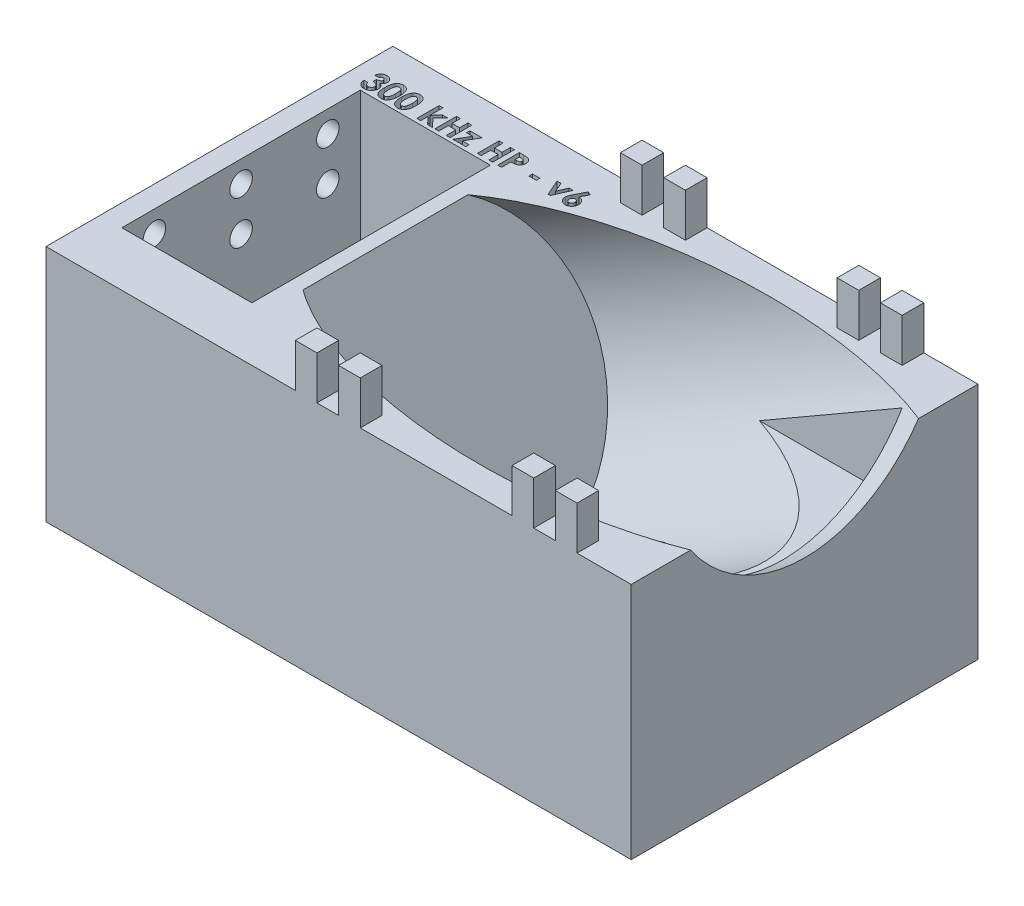
SolidWorks part; units mm, degrees
ref_plane "Front Plane" through (0, 0, 0) normal (0, 0, 1) x (1, 0, 0)
ref_plane "Top Plane" through (0, 0, 0) normal (0, 1, 0) x (1, 0, 0)
ref_plane "Right Plane" through (0, 0, 0) normal (1, 0, 0) x (0, 0, -1)
sketch "Sketch1" plane through (0, 0, 0) normal (0, 0, 1) x (1, 0, 0)
  line L1 (-139.7, -127) -> (88.9, -127)
  line L2 (-139.7, -127) -> (-139.7, 0)
  line L3 (-139.7, 0) -> (88.9, 0)
  line L4 (88.9, -127) -> (88.9, 0)
  line L5 (-139.7, -127) -> (88.9, 0) construction
  line L6 (-139.7, 0) -> (88.9, -127) construction
  point P0 (0, 0)
  dimension "D1" = 228.6
  dimension "D2" = 127
  dimension "D3" = 88.9
extrude "Boss-Extrude1" add sketch "Sketch1" along normal mid plane 101.6
sketch "Sketch10" plane through (0, -127, 0) normal (0, -1, 0) x (1, 0, 0)
  circle A0 centre (0, 0) radius 12.7
  dimension "D1" = 25.4
extrude "Cut-Extrude6" cut sketch "Sketch10" against normal through all
sketch "Sketch2" plane through (0, 0, 0) normal (0, 0, 1) x (1, 0, 0)
  line L0 (-48.125, -30.325) -> (0, -2.54) construction
  line L1 (0, 46.5867) -> (-47.9201, 18.9201)
  line L2 (-50.1425, -26.8306) -> (-69.3975, 6.5201)
  line L3 (-69.3975, 6.5201) -> (-47.9201, 18.9201)
  line L4 (-50.1425, -26.8306) -> (-48.125, -30.325)
  line L5 (-26.6476, -17.925) -> (-47.9201, 18.9201) construction
  line L7 (0, -2.54) -> (87.9882, 48.26)
  line L8 (-83.8, -2.54) -> (0, -2.54) construction
  line L10 (0, -2.54) -> (-48.125, -30.325)
  line L11 (88.9, 0) -> (-139.7, 0) construction
  line L12 (87.9882, 48.26) -> (66.7157, 85.1051)
  line L13 (0, 46.5867) -> (0, -2.54) construction
  line L17 (66.7157, 85.1051) -> (0, 46.5867)
  point P23 (-26.6476, -17.925)
  dimension "D1" = 30
  dimension "D2" = 24.8
  dimension "D3" = 2.54
  dimension "D4" = 30.77
  dimension "D5" = 42.545
  dimension "D6" = 101.6
revolve "Cut-Revolve1" cut sketch "Sketch2" angle 360 about L0
sketch "Sketch11" plane through (0, -127, 0) normal (0, -1, 0) x (1, 0, 0)
  line L1 (13, 13) -> (-13, 13)
  line L2 (13, 13) -> (13, -13)
  line L3 (13, -13) -> (-13, -13)
  line L4 (-13, 13) -> (-13, -13)
  line L5 (13, 13) -> (-13, -13) construction
  line L6 (13, -13) -> (-13, 13) construction
  point P0 (0, 0)
  dimension "D1" = 26
sketch "Sketch13" plane through (0, 0, 0) normal (0, 1, 0) x (1, 0, 0)
  line L0 (88.9, 50.8) -> (-139.7, 50.8) construction
  line L1 (-41.275, 50.8) -> (-34.925, 50.8)
  line L2 (-41.275, 50.8) -> (-41.275, 44.45)
  line L3 (-41.275, 44.45) -> (-34.925, 44.45)
  line L4 (-34.925, 50.8) -> (-34.925, 44.45)
  line L5 (0, 0) -> (42.9001, 0) construction
  line L6 (-28.575, 50.8) -> (-22.225, 50.8)
  line L7 (-28.575, 50.8) -> (-28.575, 44.45)
  line L8 (-28.575, 44.45) -> (-22.225, 44.45)
  line L9 (-22.225, 50.8) -> (-22.225, 44.45)
  line L10 (0, 0) -> (0, -29.3087) construction
  line L11 (22.225, 50.8) -> (22.225, 44.45)
  line L12 (28.575, 44.45) -> (22.225, 44.45)
  line L13 (28.575, 50.8) -> (28.575, 44.45)
  line L14 (28.575, 50.8) -> (22.225, 50.8)
  line L15 (34.925, 50.8) -> (34.925, 44.45)
  line L16 (41.275, 44.45) -> (34.925, 44.45)
  line L17 (41.275, 50.8) -> (41.275, 44.45)
  line L18 (41.275, 50.8) -> (34.925, 50.8)
  line L19 (41.275, -50.8) -> (34.925, -50.8)
  line L20 (41.275, -50.8) -> (41.275, -44.45)
  line L21 (41.275, -44.45) -> (34.925, -44.45)
  line L22 (34.925, -50.8) -> (34.925, -44.45)
  line L23 (28.575, -50.8) -> (22.225, -50.8)
  line L24 (28.575, -50.8) -> (28.575, -44.45)
  line L25 (28.575, -44.45) -> (22.225, -44.45)
  line L26 (22.225, -50.8) -> (22.225, -44.45)
  line L27 (-22.225, -50.8) -> (-22.225, -44.45)
  line L28 (-28.575, -44.45) -> (-22.225, -44.45)
  line L29 (-28.575, -50.8) -> (-28.575, -44.45)
  line L30 (-28.575, -50.8) -> (-22.225, -50.8)
  line L31 (-34.925, -50.8) -> (-34.925, -44.45)
  line L32 (-41.275, -44.45) -> (-34.925, -44.45)
  line L33 (-41.275, -50.8) -> (-41.275, -44.45)
  line L34 (-41.275, -50.8) -> (-34.925, -50.8)
  point P18 (-25.4, 50.8)
  point P20 (-38.1, 50.8)
  dimension "D1" = 25.4
  dimension "D2" = 12.7
  dimension "D3" = 6.35
extrude "Boss-Extrude3" add sketch "Sketch13" along normal blind 12.7
sketch "Sketch22" plane through (0, 0, 0) normal (0, 1, 0) x (1, 0, 0)
  line L0 (-41.275, -50.8) -> (-139.7, -50.8) construction
  line L1 (-139.7, 50.8) -> (-114.3, 50.8)
  line L2 (-139.7, 50.8) -> (-139.7, -50.8)
  line L3 (-139.7, -50.8) -> (-114.3, -50.8)
  line L4 (-114.3, 50.8) -> (-114.3, -50.8)
  dimension "D1" = 25.4
extrude "Cut-Extrude17" cut sketch "Sketch22" against normal through all
sketch "Sketch23" plane through (0, -127, 0) normal (0, -1, 0) x (1, 0, 0)
  line L0 (-127, 127) -> (127, -127) construction
  line L1 (-127, 127) -> (127, 127)
  line L2 (-127, 127) -> (-127, -127)
  line L3 (-127, -127) -> (127, -127)
  line L4 (127, 127) -> (127, -127)
  dimension "D1" = 254
  dimension "D2" = 254
extrude "Cut-Extrude18" cut sketch "Sketch23" against normal blind 57.15
sketch "Sketch21" plane through (0, 0, 0) normal (0, 1, 0) x (1, 0, 0)
  line L1 (88.9, -50.8) -> (57.15, -50.8)
  line L2 (88.9, -50.8) -> (88.9, 50.8)
  line L3 (88.9, 50.8) -> (57.15, 50.8)
  line L4 (57.15, -50.8) -> (57.15, 50.8)
  line L5 (88.9, -50.8) -> (41.275, -50.8) construction
  line L6 (88.9, 50.8) -> (41.275, 50.8) construction
  line L7 (-114.3, -50.8) -> (-114.3, 50.8) construction
  dimension "D1" = 171.45
extrude "Cut-Extrude16" cut sketch "Sketch21" against normal through all
sketch "Sketch26" plane through (0, 0, 0) normal (0, 1, 0) x (1, 0, 0)
  line L0 (57.15, 50.8) -> (57.15, 33.3829) construction
  line L1 (-38.1, -34.925) -> (50.8, -34.925)
  line L2 (-38.1, -34.925) -> (-38.1, 34.925)
  line L3 (-38.1, 34.925) -> (50.8, 34.925)
  line L4 (50.8, -34.925) -> (50.8, 34.925)
  line L5 (-114.3, -50.8) -> (-114.3, 50.8) construction
  point P4 (-38.1, 0)
  dimension "D1" = 6.35
  dimension "D2" = 76.2
  dimension "D3" = 69.85
extrude "Cut-Extrude21" cut sketch "Sketch26" against normal blind 25.4
sketch "Sketch27" plane through (-114.3, 0, 0) normal (-1, 0, 0) x (0, 0, 1)
  line L0 (50.8, 0) -> (-50.8, 0) construction
  line L1 (-25.4, -6.35) -> (25.4, -6.35) construction
  line L2 (-25.4, -6.35) -> (-25.4, -19.05) construction
  line L3 (-25.4, -19.05) -> (25.4, -19.05) construction
  line L4 (25.4, -6.35) -> (25.4, -19.05) construction
  line L7 (-25.4, -19.05) -> (-25.4, -31.75) construction
  line L8 (-25.4, -31.75) -> (25.4, -31.75) construction
  line L9 (25.4, -19.05) -> (25.4, -31.75) construction
  circle A0 centre (-25.4, -6.35) radius 3.302
  circle A1 centre (0, -6.35) radius 3.302
  circle A2 centre (0, -19.05) radius 3.302
  circle A3 centre (25.4, -6.35) radius 3.302
  circle A4 centre (25.4, -19.05) radius 3.302
  circle A5 centre (-25.4, -19.05) radius 3.302
  circle A7 centre (-25.4, -31.75) radius 3.302 [skipped]
  circle A8 centre (0, -31.75) radius 3.302 [skipped]
  circle A9 centre (25.4, -31.75) radius 3.302 [skipped]
  point P4 (0, -6.35)
  dimension "D5" = 6.604
  dimension "D8" = 25.4
  dimension "D1" = 50.8
  dimension "D2" = 12.7
  dimension "D3" = 6.35
  dimension "D4" = 12.7
  dimension "D6" = 3
  dimension "D7" = 3
extrude "Cut-Extrude22" cut sketch "Sketch27" against normal blind 25.4 and the other way through all
sketch "Sketch28" plane through (0, 0, 0) normal (0, 1, 0) x (1, 0, 0)
  line L0 (-114.3, 36.0198) -> (-43.5568, 36.0198) construction
  line L3 (-114.3, -50.8) -> (-114.3, 50.8) construction
  text T0 "<b>300 kHz HP - v6</b>" font "Century Gothic" height 6.35
extrude "Cut-Extrude23" cut sketch "Sketch28" against normal blind 3.175
sketch "Sketch30" plane through (0, -25.4, 0) normal (0, 1, 0) x (1, 0, 0)
  circle A0 centre (-95.25, 25.4) radius 3.429
  circle A2 centre (-82.55, 25.4) radius 3.429
  circle A3 centre (-82.55, 12.7) radius 3.429
  circle A4 centre (-82.55, 0) radius 3.429
  circle A5 centre (-82.55, -12.7) radius 3.429
  circle A6 centre (-82.55, -25.4) radius 3.429
  circle A7 centre (-95.25, 12.7) radius 3.429
  circle A8 centre (-95.25, 0) radius 3.429
  circle A9 centre (-95.25, -12.7) radius 3.429
  circle A10 centre (-95.25, -25.4) radius 3.429
  dimension "D1" = 6.858
  dimension "D2" = 25.4
  dimension "D3" = 95.25
  dimension "D4" = 2
  dimension "D5" = 5
extrude "Cut-Extrude24" cut sketch "Sketch30" against normal through all
sketch "Sketch31" plane through (0, -25.4, 0) normal (0, 1, 0) x (1, 0, 0)
  line L0 (-107.95, -34.925) -> (-44.1937, -34.925) construction
  line L1 (-107.95, 34.925) -> (-69.85, 34.925)
  line L2 (-107.95, 34.925) -> (-107.95, -34.925)
  line L3 (-107.95, -34.925) -> (-69.85, -34.925)
  line L4 (-69.85, 34.925) -> (-69.85, -34.925)
  line L5 (-114.3, -50.8) -> (-114.3, 50.8) construction
  line L6 (-41.275, 50.8) -> (-114.3, 50.8) construction
  point P7 (0, 0)
  dimension "D1" = 38.1
  dimension "D2" = 6.35
  dimension "D3" = 15.875
extrude "Cut-Extrude25" cut sketch "Sketch31" against normal offset from surface 6.35 and the other way through all up to face at (-82.55, -69.85, 28.829)
